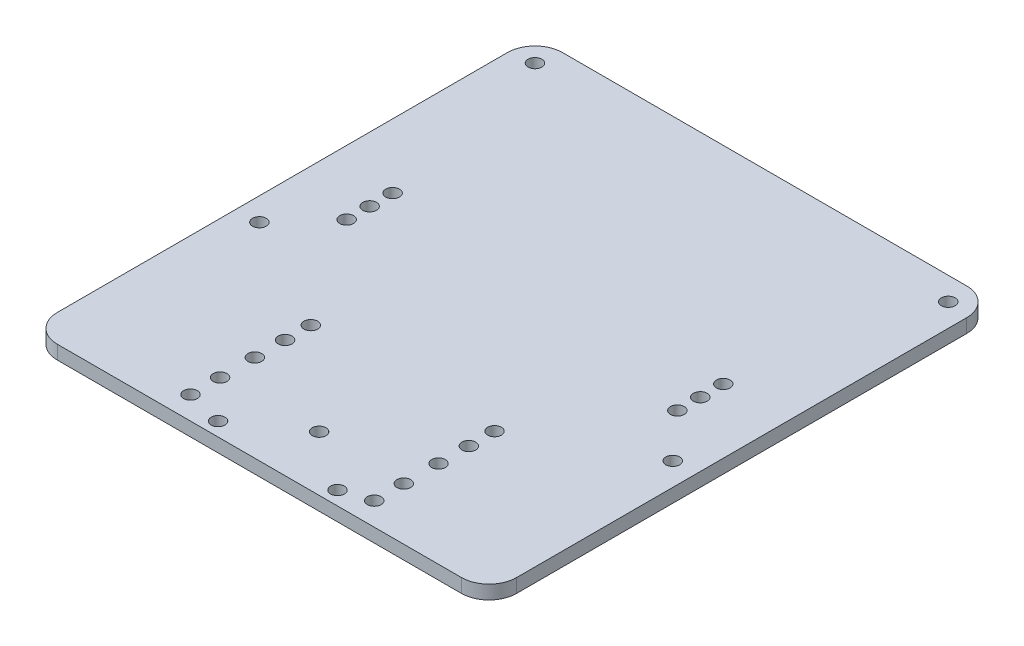
SolidWorks part; units mm, degrees
ref_plane "Front Plane" through (0, 0, 0) normal (0, 0, 1) x (1, 0, 0)
ref_plane "Top Plane" through (0, 0, 0) normal (0, 1, 0) x (1, 0, 0)
ref_plane "Right Plane" through (0, 0, 0) normal (1, 0, 0) x (0, 0, -1)
sketch "Sketch1" plane through (0, 0, 0) normal (0, 1, 0) x (1, 0, 0)
  line L1 (-50, 35) -> (50, 35)
  line L2 (-50, 35) -> (-50, -35)
  line L3 (-50, -35) -> (50, -35)
  line L4 (50, 35) -> (50, -35)
  line L5 (-50, 35) -> (50, -35) construction
  line L6 (-50, -35) -> (50, 35) construction
  point P0 (0, 0)
  dimension "D1" = 100
  dimension "D2" = 70
extrude "Boss-Extrude1" add sketch "Sketch1" along normal blind 3
sketch "Sketch2" plane through (0, 0, 0) normal (0, 1, 0) x (1, 0, 0)
  line L0 (-50, -35) -> (50, -35) construction
  circle A0 centre (-45, -30) radius 1.5
  circle A1 centre (45, -30) radius 1.5
  circle A2 centre (45, 30) radius 1.5
  circle A3 centre (-45, 30) radius 1.5
  circle A4 centre (-36, -20) radius 1.5
  circle A5 centre (36, -20) radius 1.5
  circle A6 centre (-36, -10) radius 1.5
  circle A7 centre (36, -10) radius 1.5
  circle A8 centre (-36, -15) radius 1.5
  circle A9 centre (36, -15) radius 1.5
  dimension "D1" = 3
  dimension "D2" = 3
  dimension "D3" = 3
  dimension "D4" = 3
  dimension "D10" = 3
  dimension "D11" = 3
  dimension "D14" = 3
  dimension "D15" = 3
  dimension "D17" = 3
  dimension "D18" = 3
  dimension "D5" = 90
  dimension "D6" = 60
  dimension "D7" = 30
  dimension "D8" = 45
  dimension "D9" = 72
  dimension "D12" = 36
  dimension "D13" = 15
  dimension "D16" = 10
  dimension "D19" = 5
extrude "Cut-Extrude3" cut sketch "Sketch2" along normal blind 4
sketch "Sketch3" plane through (0, 0, 0) normal (0, 1, 0) x (1, 0, 0)
  line L0 (-50, -35) -> (50, -35) construction
  line L1 (-25, -75) -> (25, -75)
  line L2 (-25, -75) -> (-25, -35)
  line L3 (-25, -35) -> (25, -35)
  line L4 (25, -75) -> (25, -35)
  line L5 (-25, -75) -> (25, -35) construction
  line L6 (-25, -35) -> (25, -75) construction
  point P0 (0, -55)
  dimension "D1" = 50
  dimension "D2" = 40
extrude "Boss-Extrude2" add sketch "Sketch3" along normal blind 3
sketch "Sketch4" plane through (0, 0, 0) normal (0, 1, 0) x (1, 0, 0)
  line L0 (-50, -35) -> (-25, -35) construction
  circle A0 centre (-20, -70) radius 1.5
  circle A1 centre (20, -70) radius 1.5
  circle A2 centre (-20, -56) radius 1.5
  circle A3 centre (20, -56) radius 1.5
  circle A4 centre (1, -63) radius 1.5
  dimension "D4" = 3
  dimension "D5" = 3
  dimension "D6" = 3
  dimension "D7" = 3
  dimension "D9" = 3
  dimension "D1" = 35
  dimension "D2" = 40
  dimension "D3" = 20
  dimension "D8" = 21
  dimension "D10" = 7
  dimension "D11" = 21
extrude "Cut-Extrude4" cut sketch "Sketch4" along normal up to next
sketch "Sketch5" plane through (0, 0, 0) normal (0, -1, 0) x (1, 0, 0)
  circle A0 centre (69, 26.625) radius 1.5
  circle A1 centre (69, 26.625) radius 1.5 construction
  dimension "D1" = 3
extrude "Cut-Extrude5" cut sketch "Sketch5" against normal up to next
sketch "Sketch6" plane through (0, 0, 0) normal (0, -1, 0) x (1, 0, 0)
  line L0 (-25, 35) -> (-25, 75) construction
  line L1 (25, 75) -> (25, 35) construction
  circle A0 centre (-20, 63.5632) radius 1.5
  circle A1 centre (20, 63.5632) radius 1.5
  circle A2 centre (20, 43.8082) radius 1.5
  circle A3 centre (-20, 49.4058) radius 1.5
  circle A4 centre (-20, 43.8082) radius 1.5
  circle A5 centre (20, 49.4058) radius 1.5
  dimension "D1" = 3
  dimension "D2" = 3
  dimension "D3" = 3
  dimension "D7" = 3
  dimension "D8" = 3
  dimension "D9" = 3
  dimension "D4" = 5
  dimension "D5" = 5
  dimension "D6" = 5
  dimension "D10" = 5
extrude "Cut-Extrude6" cut sketch "Sketch6" against normal up to next
sketch "Sketch8" plane through (0, 0, 0) normal (0, 1, 0) x (1, 0, 0)
  line L0 (-25, -75) -> (25, -75) construction
  circle A0 centre (-12, -72) radius 1.5
  circle A1 centre (14, -72) radius 1.5
  circle A2 centre (1, -63) radius 1.5 construction
  dimension "D1" = 13
  dimension "D3" = 3
  dimension "D4" = 3
  dimension "D2" = 13
  dimension "D5" = 3
extrude "Cut-Extrude7" cut sketch "Sketch8" along normal up to next
sketch "Sketch9" plane through (0, 0, 0) normal (0, 1, 0) x (1, 0, 0)
  line L0 (-25, -35) -> (-25, -75) construction
  line L1 (25, -75) -> (50, -75)
  line L2 (25, -75) -> (25, -35)
  line L3 (25, -35) -> (50, -35)
  line L4 (50, -75) -> (50, -35)
  line L5 (25, -75) -> (50, -35) construction
  line L6 (25, -35) -> (50, -75) construction
  line L7 (-50, -75) -> (-25, -75)
  line L8 (-50, -75) -> (-50, -35)
  line L9 (-50, -35) -> (-25, -35)
  line L10 (-25, -75) -> (-25, -35)
  line L11 (-50, -75) -> (-25, -35) construction
  line L12 (-50, -35) -> (-25, -75) construction
  line L13 (31.2926, -30.9491) -> (41.4066, -30.9491)
  line L14 (31.2926, -30.9491) -> (31.2926, -22.6741)
  line L15 (31.2926, -22.6741) -> (41.4066, -22.6741)
  line L16 (41.4066, -30.9491) -> (41.4066, -22.6741)
  line L17 (31.2926, -30.9491) -> (41.4066, -22.6741) construction
  line L18 (31.2926, -22.6741) -> (41.4066, -30.9491) construction
  line L20 (-25, -75) -> (25, -75) construction
  line L21 (25, -75) -> (25, -35) construction
  line L24 (50, -35) -> (50, 35) construction
  line L25 (-50, 35) -> (-50, -35) construction
  line L26 (-50, -35) -> (-25, -35) construction
  line L27 (25, -35) -> (50, -35) construction
  point P0 (37.5, -55)
  point P5 (-37.5, -55)
  point P10 (36.3496, -26.8116)
extrude "Boss-Extrude3" add sketch "Sketch9" along normal up to vertex (3 mm away)
fillet "Fillet1" radius 6 4 edges at (-50, 1.5, -35) (50, 1.5, -35) (50, 1.5, 75) (-50, 1.5, 75)
